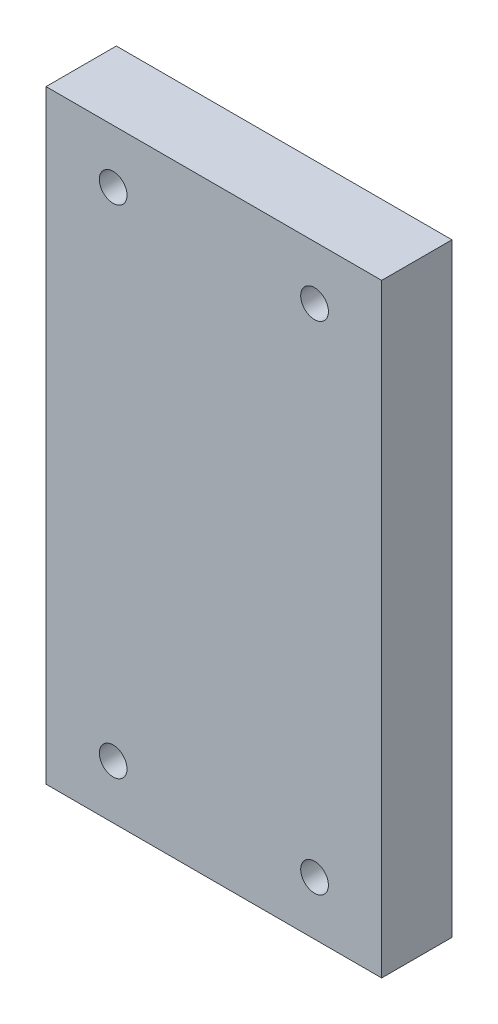
SolidWorks part; units mm, degrees
ref_plane "Front Plane" through (0, 0, 0) normal (0, 0, 1) x (1, 0, 0)
ref_plane "Top Plane" through (0, 0, 0) normal (0, 1, 0) x (1, 0, 0)
ref_plane "Right Plane" through (0, 0, 0) normal (1, 0, 0) x (0, 0, -1)
sketch "Sketch1" plane through (0, 0, 0) normal (0, 0, 1) x (1, 0, 0)
  line L1 (0, 0) -> (50, 0)
  line L2 (0, 0) -> (0, 90)
  line L3 (0, 90) -> (50, 90)
  line L4 (50, 0) -> (50, 90)
  circle A0 centre (40, 8) radius 2.065
  circle A1 centre (10, 8) radius 2.065
  circle A2 centre (40, 82) radius 2.065
  circle A3 centre (10, 82) radius 2.065
  dimension "D8" = 4.13
  dimension "D9" = 4.13
  dimension "D10" = 4.13
  dimension "D11" = 4.13
  dimension "D1" = 90
  dimension "D2" = 50
  dimension "D3" = 30
  dimension "D4" = 74
  dimension "D5" = 30
  dimension "D6" = 8
  dimension "D7" = 10
extrude "Boss-Extrude1" add sketch "Sketch1" along normal blind 10.47
